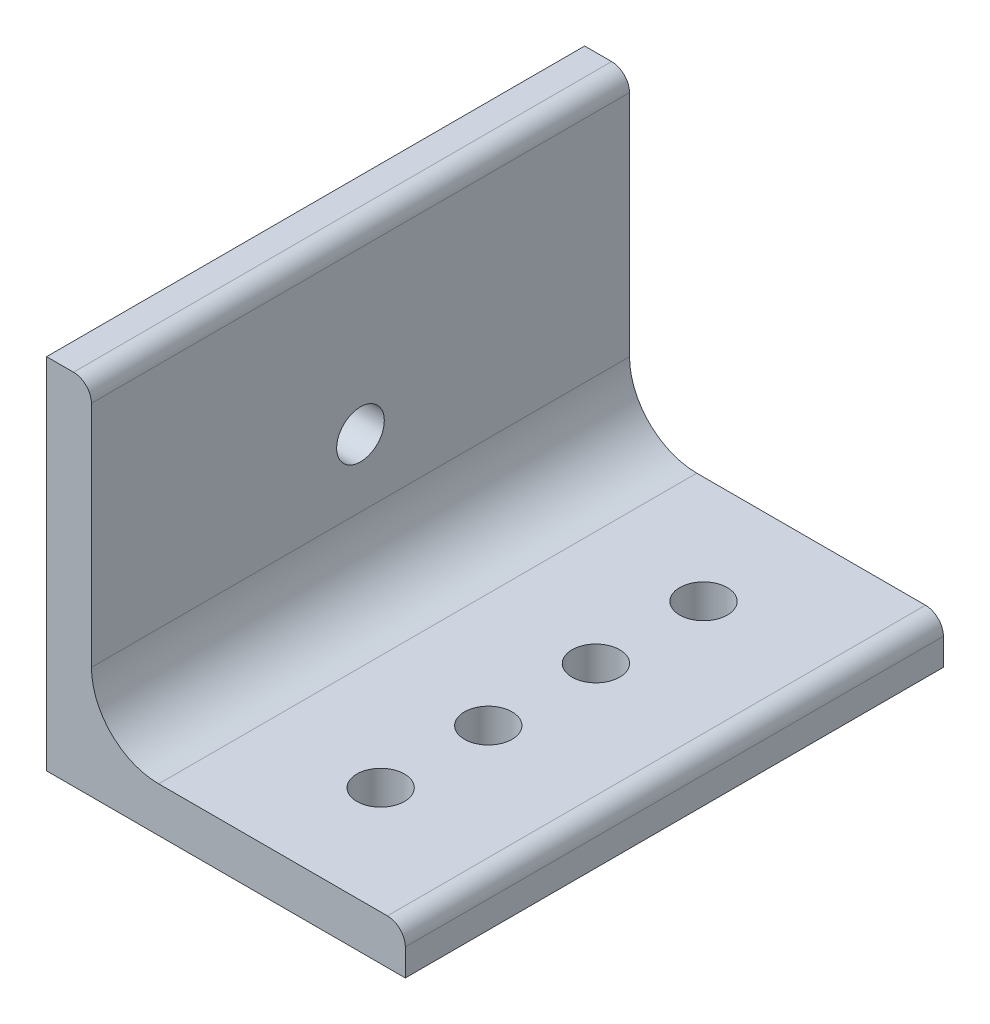
SolidWorks part; units mm, degrees
ref_plane "Front" through (0, 0, 0) normal (0, 0, 1) x (1, 0, 0)
ref_plane "Top" through (0, 0, 0) normal (0, 1, 0) x (1, 0, 0)
ref_plane "Right" through (0, 0, 0) normal (1, 0, 0) x (0, 0, -1)
sketch "Sketch1" plane through (0, 0, 0) normal (0, 0, 1) x (1, 0, 0)
  line L0 (0, 0) -> (0, 88.9)
  line L1 (0, 88.9) -> (-12.7, 88.9)
  line L2 (-12.7, 88.9) -> (-12.7, -12.7)
  line L3 (-12.7, -12.7) -> (88.9, -12.7)
  line L4 (88.9, -12.7) -> (88.9, 0)
  line L5 (88.9, 0) -> (0, 0)
  dimension "Outside Height" = 101.6
  dimension "Outside Width" = 101.6
  dimension "Wall Thickness" = 12.7
  dimension "Inside Width" = 88.9
  dimension "Inside Height" = 88.9
sketch "Sketch2" plane through (0, 0, 0) normal (1, 0, 0) x (0, 0, -1)
  line L0 (-76.2, 0) -> (76.2, 0) construction
  line L1 (76.2, -12.7) -> (-76.2, -12.7) construction
  point P2 (0, 0)
  point P3 (0, -12.7)
  point P5 (76.2, 0)
  point P6 (35.56, -12.7)
  point P9 (0, -12.7)
  point P10 (-76.2, -12.7)
  point P11 (76.2, -12.7)
  point P12 (-76.2, 0)
  point P14 (-35.56, -12.7)
  dimension "Length" = 152.4
  dimension "D1" = 111.76
  dimension "D2" = 111.76
sketch "Sketch3" plane through (0, 0, 0) normal (0, 0, 1) x (1, 0, 0)
  line L0 (0, 0) -> (0, 88.9) construction
  line L1 (0, 88.9) -> (-12.7, 88.9) construction
  line L2 (-12.7, 88.9) -> (-12.7, -12.7) construction
  line L3 (-12.7, -12.7) -> (88.9, -12.7) construction
  line L4 (88.9, -12.7) -> (88.9, 0) construction
  line L5 (88.9, 0) -> (0, 0) construction
  line L6 (0, 19.05) -> (0, 83.82)
  line L7 (-5.08, 88.9) -> (-12.7, 88.9)
  line L8 (-12.7, 88.9) -> (-12.7, -12.7)
  line L9 (-12.7, -12.7) -> (88.9, -12.7)
  line L10 (88.9, -12.7) -> (88.9, -5.08)
  line L11 (83.82, 0) -> (19.05, 0)
  arc A0 (0, 19.05) -> (19.05, 0) centre (19.05, 19.05) ccw
  arc A1 (88.9, -5.08) -> (83.82, 0) centre (83.82, -5.08) ccw
  arc A2 (0, 83.82) -> (-5.08, 88.9) centre (-5.08, 83.82) ccw
  dimension "D1" = 5.08
  dimension "D2" = 19.05
extrude "Boss-Extrude1" add sketch "Sketch3" along normal up to vertex (76.2 mm away) and the other way up to vertex (76.2 mm away) up to point (0, 0, 76.2) other way up to point (0, 0, -76.2)
sketch "Sketch4" plane through (0, 0, 0) normal (1, 0, 0) x (0, 0, -1)
  line L0 (-76.2, -12.7) -> (76.2, -12.7) construction
  line L1 (0, 55.88) -> (0, -55.88) construction
  point P0 (0, 38.1)
  dimension "D1" = 50.8
hole_wizard "M12 Clearance Hole1" positions "Sketch4" profile "Sketch5" hole size "M12" standard "ANSI Metric" end condition through all
sketch "Sketch5" plane through (0, 38.1, 0) normal (0, 1, 0) x (0, 0, -1)
  line L0 (0, 0) -> (0, 12.7)
  line L1 (0, 12.7) -> (6.75, 12.7)
  line L2 (6.75, 12.7) -> (6.75, 0)
  line L5 (6.75, 0) -> (0, 0)
  line L11 (0, -6.35) -> (0, 107.95) construction
  dimension "Thru Hole Dia." = 13.5
  dimension "Thru Hole Depth" = 12.7
sketch "Sketch6" plane through (0, 0, 0) normal (0, 1, 0) x (1, 0, 0)
  line L0 (83.82, 76.2) -> (19.05, 76.2) construction
  line L1 (51.435, 76.2) -> (51.435, 45.72) construction
  line L2 (51.435, 45.72) -> (51.435, 15.24) construction
  line L3 (51.435, 15.24) -> (51.435, -15.24) construction
  line L4 (51.435, -15.24) -> (51.435, -45.72) construction
  line L6 (51.435, -45.72) -> (51.435, -76.2) construction
  line L7 (83.82, -76.2) -> (19.05, -76.2) construction
  point P12 (51.435, 45.72)
  point P13 (51.435, 15.24)
  point P14 (51.435, -15.24)
  point P27 (51.435, -45.72)
hole_wizard "1/2 Clearance Hole1" positions "Sketch6" profile "Sketch7" hole size "1/2" standard "ANSI Inch" end condition through all
sketch "Sketch7" plane through (51.435, 0, 45.72) normal (1, 0, 0) x (0, 0, 1)
  line L0 (0, 0) -> (0, 12.7)
  line L1 (0, 12.7) -> (6.7462, 12.7)
  line L2 (6.7462, 12.7) -> (6.7462, 0)
  line L5 (6.7462, 0) -> (0, 0)
  line L11 (0, -6.35) -> (0, 107.95) construction
  dimension "Thru Hole Dia." = 13.4925
  dimension "Thru Hole Depth" = 12.7
equation "\"D1@Sketch3\"=\"Wall Thickness@Sketch1\"*0.4"
equation "\"D2@Sketch3\"=\"Wall Thickness@Sketch1\"*1.5"
equation "\"D1@Sketch2\" = \"Outside Width@Sketch1\" * 1.1"
equation "\"D2@Sketch2\"=\"D1@Sketch2\""
